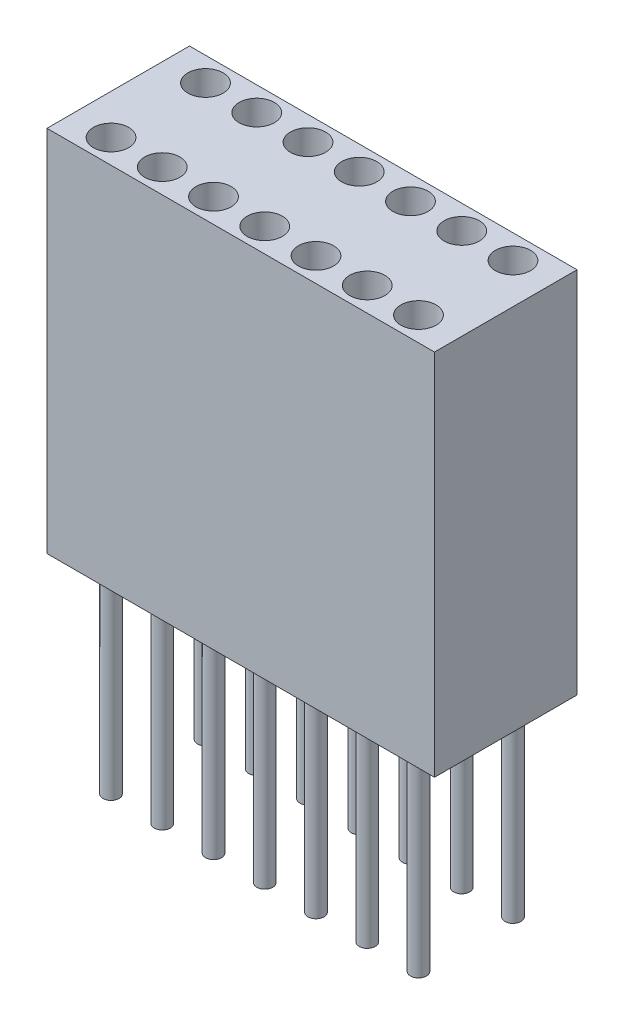
SolidWorks part; units mm, degrees
material "PEI"
ref_plane "Front Plane" through (0, 0, 0) normal (0, 0, 1) x (1, 0, 0)
ref_plane "Top Plane" through (0, 0, 0) normal (0, 1, 0) x (1, 0, 0)
ref_plane "Right Plane" through (0, 0, 0) normal (1, 0, 0) x (0, 0, -1)
sketch "Sketch2" plane through (0, 0, 0) normal (0, 1, 0) x (1, 0, 0)
  line L1 (0, 0) -> (4.84, 0)
  line L2 (0, 0) -> (0, 1.78)
  line L3 (0, 1.78) -> (4.84, 1.78)
  line L4 (4.84, 0) -> (4.84, 1.78)
  dimension "D1" = 4.84
  dimension "D2" = 1.78
extrude "Boss-Extrude1" add sketch "Sketch2" along normal blind 4.6
sketch "Sketch3" plane through (0, 4.6, 0) normal (0, 1, 0) x (1, 0, 0)
  line L0 (4.84, 1.78) -> (0, 1.78) construction
  line L1 (0, 1.78) -> (0, 0) construction
  circle A0 centre (0.5, 1.48) radius 0.22
  circle A1 centre (1.14, 1.48) radius 0.22
  circle A2 centre (1.78, 1.48) radius 0.22
  circle A3 centre (2.42, 1.48) radius 0.22
  circle A4 centre (3.06, 1.48) radius 0.22
  circle A5 centre (3.7, 1.48) radius 0.22
  circle A6 centre (4.34, 1.48) radius 0.22
  circle A7 centre (0.5, 0.3) radius 0.22
  circle A8 centre (1.14, 0.3) radius 0.22
  circle A9 centre (1.78, 0.3) radius 0.22
  circle A10 centre (2.42, 0.3) radius 0.22
  circle A11 centre (3.06, 0.3) radius 0.22
  circle A12 centre (3.7, 0.3) radius 0.22
  circle A13 centre (4.34, 0.3) radius 0.22
  dimension "D1" = 7
  dimension "D3" = 0.3
  dimension "D4" = 0.5
  dimension "D2" = 2
extrude "Cut-Extrude1" cut sketch "Sketch3" against normal blind 4.5
sketch "Sketch5" plane through (0, 0, 0) normal (0, -1, 0) x (1, 0, 0)
  circle A0 centre (0.5, -0.3) radius 0.1
  circle A1 centre (1.14, -0.3) radius 0.1
  circle A2 centre (1.78, -0.3) radius 0.1
  circle A3 centre (2.42, -0.3) radius 0.1
  circle A4 centre (3.06, -0.3) radius 0.1
  circle A5 centre (3.7, -0.3) radius 0.1
  circle A6 centre (4.34, -0.3) radius 0.1
  circle A7 centre (0.5, -1.48) radius 0.1
  circle A8 centre (1.14, -1.48) radius 0.1
  circle A9 centre (1.78, -1.48) radius 0.1
  circle A10 centre (2.42, -1.48) radius 0.1
  circle A11 centre (3.06, -1.48) radius 0.1
  circle A12 centre (3.7, -1.48) radius 0.1
  circle A13 centre (4.34, -1.48) radius 0.1
  dimension "D1" = 7
  dimension "D3" = 0.3
  dimension "D4" = 0.5
  dimension "D2" = 2
extrude "Boss-Extrude2" add sketch "Sketch5" along normal blind 2.5
